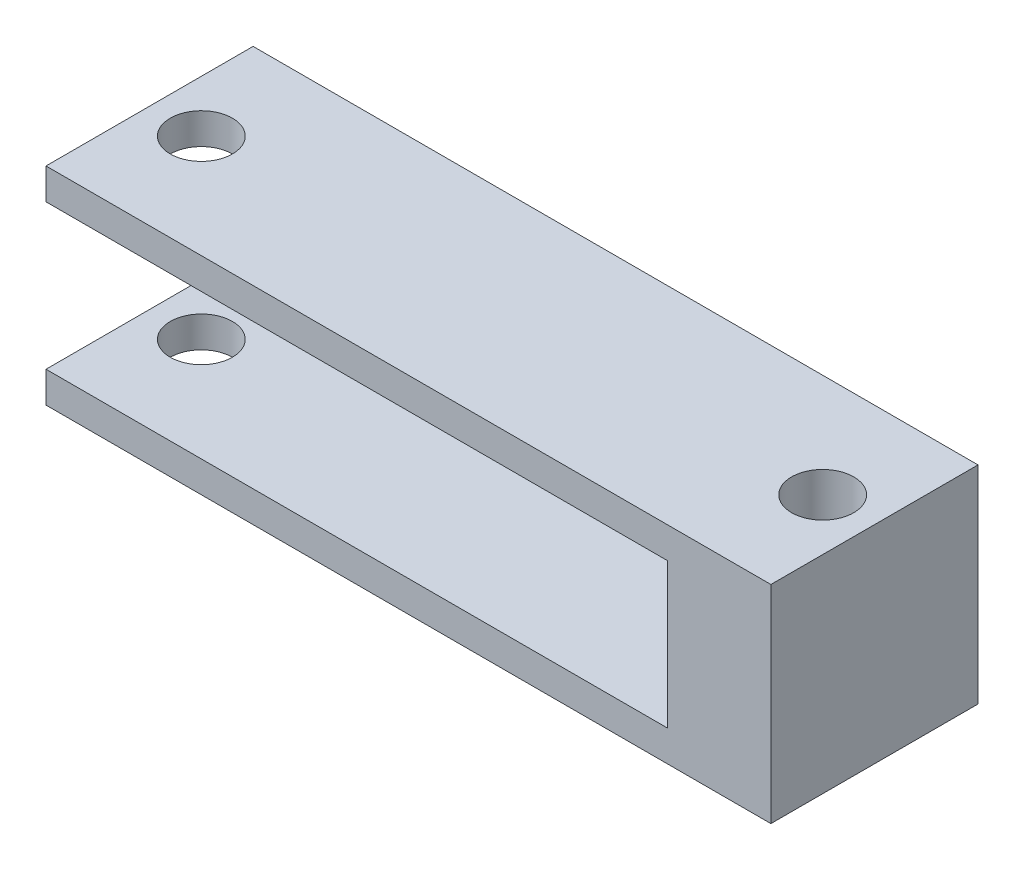
SolidWorks part; units mm, degrees
ref_plane "Front Plane" through (0, 0, 0) normal (0, 0, 1) x (1, 0, 0)
ref_plane "Top Plane" through (0, 0, 0) normal (0, 1, 0) x (1, 0, 0)
ref_plane "Right Plane" through (0, 0, 0) normal (1, 0, 0) x (0, 0, -1)
sketch "Sketch1" plane through (0, 0, 0) normal (0, 1, 0) x (1, 0, 0)
  line L1 (-17.5, 5) -> (17.5, 5)
  line L2 (-17.5, 5) -> (-17.5, -5)
  line L3 (-17.5, -5) -> (17.5, -5)
  line L4 (17.5, 5) -> (17.5, -5)
  line L5 (-17.5, 5) -> (17.5, -5) construction
  line L6 (-17.5, -5) -> (17.5, 5) construction
  circle A0 centre (-15, 0) radius 1.5
  circle A1 centre (15, 0) radius 1.5
  point P0 (0, 0)
  dimension "D2" = 3
  dimension "D1" = 10
  dimension "D3" = 30
  dimension "D4" = 35
  dimension "D5" = 15
extrude "Boss-Extrude1" add sketch "Sketch1" along normal blind 10
sketch "Sketch2" plane through (0, 0, 5) normal (0, 0, 1) x (1, 0, 0)
  line L0 (-17.5, 10) -> (-17.5, 0) construction
  line L1 (12.5, 8.5) -> (-47.5, 8.5)
  line L2 (12.5, 8.5) -> (12.5, 1.5)
  line L3 (12.5, 1.5) -> (-47.5, 1.5)
  line L4 (-47.5, 8.5) -> (-47.5, 1.5)
  line L5 (12.5, 8.5) -> (-47.5, 1.5) construction
  line L6 (12.5, 1.5) -> (-47.5, 8.5) construction
  point P0 (-17.5, 5)
  dimension "D1" = 7
  dimension "D2" = 30
extrude "Cut-Extrude1" cut sketch "Sketch2" against normal blind 10
